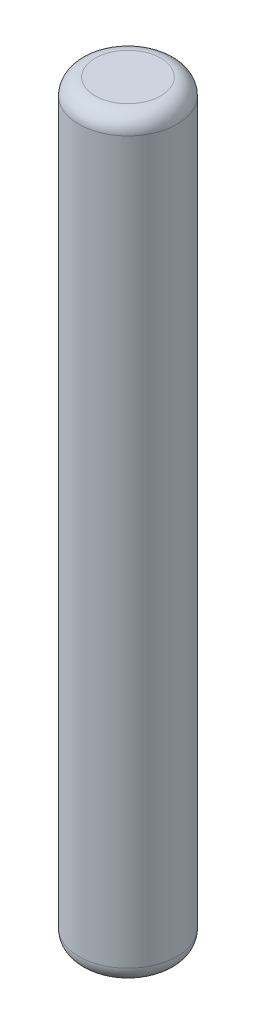
SolidWorks part; units mm, degrees
material "1060-H12"
ref_plane "前视基准面" through (0, 0, 0) normal (0, 0, 1) x (1, 0, 0)
ref_plane "上视基准面" through (0, 0, 0) normal (0, 1, 0) x (1, 0, 0)
ref_plane "右视基准面" through (0, 0, 0) normal (1, 0, 0) x (0, 0, -1)
sketch "草图2" plane through (0, 0, 0) normal (0, 1, 0) x (1, 0, 0)
  circle A0 centre (0, 0) radius 1.5
  dimension "D1" = 3
extrude "凸台-拉伸1" add sketch "草图2" along normal mid plane 23
fillet "圆角4" radius 0.5 2 edges at (0, -11.5, 1.5) (0, 11.5, 1.5)
